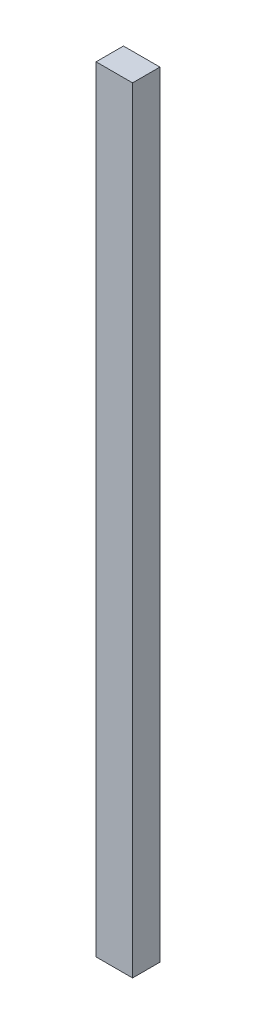
SolidWorks part; units mm, degrees
ref_plane "前视" through (0, 0, 0) normal (0, 0, 1) x (1, 0, 0)
ref_plane "上视" through (0, 0, 0) normal (0, 1, 0) x (1, 0, 0)
ref_plane "右视" through (0, 0, 0) normal (1, 0, 0) x (0, 0, -1)
sketch "草图1" plane through (0, 0, 0) normal (0, 0, 1) x (1, 0, 0)
  line L1 (0, 0) -> (4, 0)
  line L2 (0, 0) -> (0, 85)
  line L3 (0, 85) -> (4, 85)
  line L4 (4, 0) -> (4, 85)
  dimension "D1" = 85
  dimension "D2" = 4
extrude "凸台-拉伸1" add sketch "草图1" along normal blind 3
